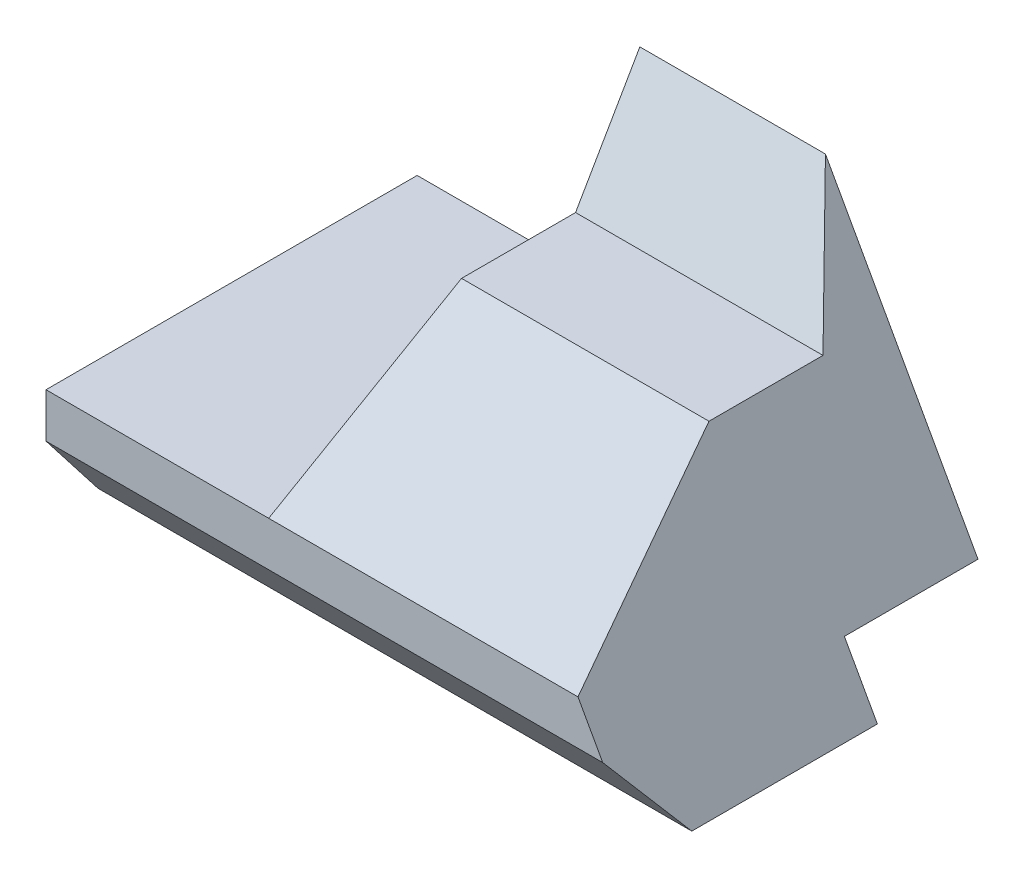
SolidWorks part; units mm, degrees
ref_plane "Plano frontal" through (0, 0, 0) normal (0, 0, 1) x (1, 0, 0)
ref_plane "Plano superior" through (0, 0, 0) normal (0, 1, 0) x (1, 0, 0)
ref_plane "Plano direito" through (0, 0, 0) normal (1, 0, 0) x (0, 0, -1)
sketch "Esboço1" plane through (0, 0, 0) normal (1, 0, 0) x (0, 0, -1)
  line L0 (-50, 7) -> (-24.0192, 22)
  line L1 (-24.0192, 22) -> (-8.6603, 22)
  line L2 (-8.6603, 22) -> (0, 37)
  line L3 (0, 37) -> (0, 0)
  line L4 (0, 0) -> (-18, 0)
  line L5 (-18, 0) -> (-18, -8)
  line L6 (-18, -8) -> (-43, -8)
  line L7 (-43, -8) -> (-50, 1)
  line L8 (-50, 1) -> (-50, 7)
  point P6 (-60.1566, 3.0124)
  point P10 (-39.1612, 18.5308)
  point P11 (-32.7712, 31.3107)
  point P12 (0, 0)
  point P14 (-50, 0)
  point P15 (0, 0)
  dimension "D1" = 30
  dimension "D2" = 120
  dimension "D3" = 45
  dimension "D4" = 8
  dimension "D5" = 15
  dimension "D6" = 7
  dimension "D7" = 32
  dimension "D8" = 50
  dimension "D9" = 15
  dimension "D10" = 9
extrude "Ressalto-extrusão1" add sketch "Esboço1" against normal blind 80
sketch "Esboço2" plane through (0, 0, 0) normal (0, 0, 1) x (1, 0, 0)
  line L0 (-50, 37) -> (-50, 7)
  line L1 (-80, 37) -> (0, 37) construction
  line L3 (-50, 7) -> (-80, 7)
  line L4 (-80, 7) -> (-80, 37)
  line L5 (-80, 37) -> (-50, 37)
  dimension "D1" = 30
  dimension "D2" = 30
extrude "Corte-extrusão2" cut sketch "Esboço2" along normal up to next and the other way through all
sketch "Esboço3" plane through (0, 0, 0) normal (0, 0, 1) x (1, 0, 0)
  line L0 (-25, 37) -> (0, -8)
  line L1 (-50, 37) -> (0, 37) construction
  line L5 (-25, 37) -> (0, 37)
  line L6 (0, 37) -> (0, -8)
  dimension "D1" = 25
extrude "Corte-extrusão3" cut sketch "Esboço3" along normal up to next
